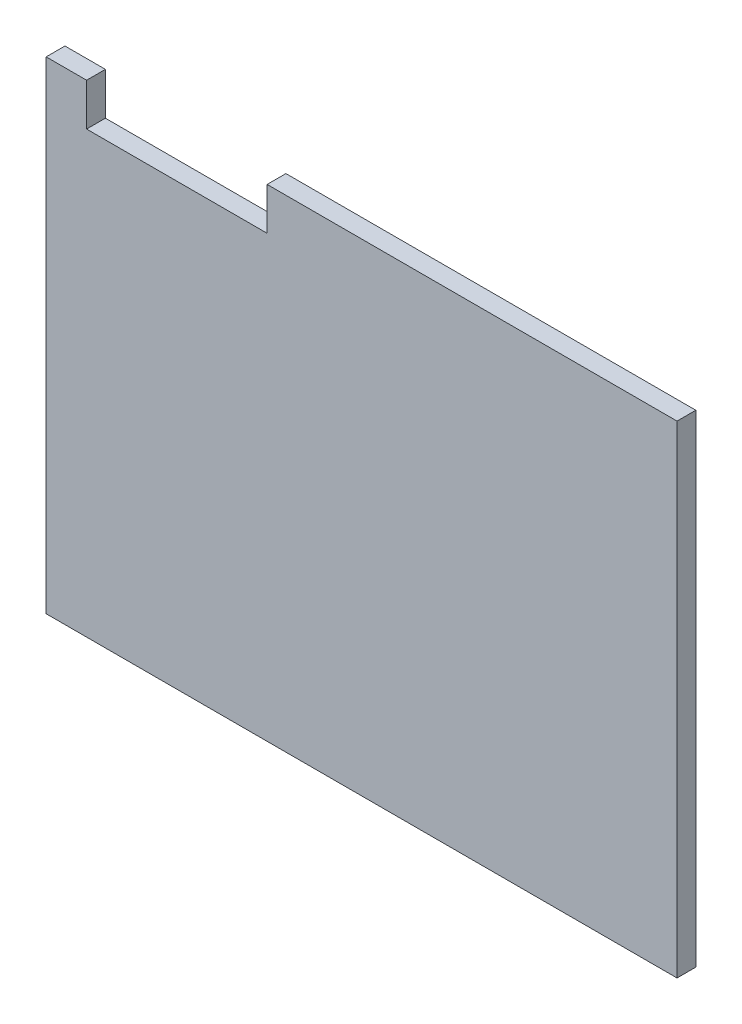
SolidWorks part; units mm, degrees
ref_plane "Front Plane" through (0, 0, 0) normal (0, 0, 1) x (1, 0, 0)
ref_plane "Top Plane" through (0, 0, 0) normal (0, 1, 0) x (1, 0, 0)
ref_plane "Right Plane" through (0, 0, 0) normal (1, 0, 0) x (0, 0, -1)
sketch "Sketch2" plane through (0, 0, 0) normal (0, 0, 1) x (1, 0, 0)
  line L16 (-88.9457, -6.4) -> (-88.9457, -1.9)
  line L17 (-88.9457, -1.9) -> (-93.6457, -1.9)
  line L18 (-93.6457, -1.9) -> (-93.6457, -44.6)
  line L19 (-93.6457, -44.6) -> (-26.1457, -44.6)
  line L20 (-26.1457, -44.6) -> (-26.1457, -1.9)
  line L21 (-26.1457, -1.9) -> (-70.1457, -1.9)
  line L22 (-70.1457, -1.9) -> (-70.1457, -6.4)
  line L23 (-70.1457, -6.4) -> (-88.9457, -6.4)
  line L24 (-88.9457, -6.4) -> (-88.9457, -1.9)
  line L25 (-88.9457, -1.9) -> (-93.6457, -1.9)
  line L26 (-93.6457, -1.9) -> (-93.6457, -44.6)
  line L27 (-93.6457, -44.6) -> (-26.1457, -44.6)
  line L28 (-26.1457, -44.6) -> (-26.1457, -1.9)
  line L29 (-26.1457, -1.9) -> (-70.1457, -1.9)
  line L30 (-70.1457, -1.9) -> (-70.1457, -6.4)
  line L31 (-70.1457, -6.4) -> (-88.9457, -6.4)
  dimension "D1" = 0.4
extrude "Boss-Extrude1" add sketch "Sketch2" along normal blind 2 contours L27 L28 L29 L30 L31 L24 L25 L26
sketch "Sketch3" plane through (0, 0, 2) normal (0, 0, 1) x (1, 0, 0)
  line L8 (-93.6457, -1.9) -> (-93.6457, -44.6)
  line L9 (-93.4457, -2.1) -> (-93.4457, -44.4)
  line L10 (-93.4457, -44.4) -> (-26.3457, -44.4)
  line L11 (-26.3457, -44.4) -> (-26.3457, -2.1)
  line L12 (-26.3457, -2.1) -> (-69.9457, -2.1)
  line L13 (-69.9457, -2.1) -> (-69.9457, -6.6)
  line L14 (-69.9457, -6.6) -> (-89.1457, -6.6)
  line L15 (-89.1457, -6.6) -> (-89.1457, -2.1)
  line L16 (-93.6457, -1.9) -> (-93.6457, -44.6)
  line L17 (-93.6457, -44.6) -> (-26.1457, -44.6)
  line L18 (-26.1457, -44.6) -> (-26.1457, -1.9)
  line L19 (-26.1457, -1.9) -> (-70.1457, -1.9)
  line L20 (-70.1457, -1.9) -> (-70.1457, -6.4)
  line L21 (-70.1457, -6.4) -> (-88.9457, -6.4)
  line L22 (-88.9457, -6.4) -> (-88.9457, -1.9)
  line L23 (-88.9457, -1.9) -> (-93.6457, -1.9)
  line L24 (-93.6457, -1.9) -> (-93.6457, -44.6)
  line L25 (-93.6457, -44.6) -> (-26.1457, -44.6)
  line L26 (-26.1457, -44.6) -> (-26.1457, -1.9)
  line L27 (-26.1457, -1.9) -> (-70.1457, -1.9)
  line L28 (-70.1457, -1.9) -> (-70.1457, -6.4)
  line L29 (-70.1457, -6.4) -> (-88.9457, -6.4)
  line L30 (-88.9457, -6.4) -> (-88.9457, -1.9)
  line L31 (-88.9457, -1.9) -> (-93.6457, -1.9)
  line L32 (-89.1457, -2.1) -> (-93.4457, -2.1)
  line M17 (-93.6457, -1.9) -> (-93.6457, -44.6)
  line M18 (-93.6457, -44.6) -> (-26.1457, -44.6)
  line M19 (-26.1457, -44.6) -> (-26.1457, -1.9)
  line M20 (-26.1457, -1.9) -> (-70.1457, -1.9)
  line M21 (-70.1457, -1.9) -> (-70.1457, -6.4)
  line M22 (-70.1457, -6.4) -> (-88.9457, -6.4)
  line M23 (-88.9457, -6.4) -> (-88.9457, -1.9)
  line M24 (-88.9457, -1.9) -> (-93.6457, -1.9)
  dimension "D1" = 0
  dimension "D2" = 0
  dimension "D3" = 0.2
extrude "Cut-Extrude1" cut sketch "Sketch3" against normal through all contours L32 L15 L14 L13 L12 L11 L10 L9 M24 M17 M18 M19 M20 M21 M22 M23
sketch "Sketch4" plane through (0, 0, 2) normal (0, 0, 1) x (1, 0, 0)
  line L1 (-93.4457, -44.4) -> (-26.3457, -44.4)
  line L2 (-93.4457, -44.4) -> (-93.4457, -53.4)
  line L3 (-93.4457, -53.4) -> (-26.3457, -53.4)
  line L4 (-26.3457, -44.4) -> (-26.3457, -53.4)
  dimension "D1" = 9
extrude "Boss-Extrude2" add sketch "Sketch4" against normal up to surface (2 mm away) up to face at (-69.7207, -13.8, 0)
